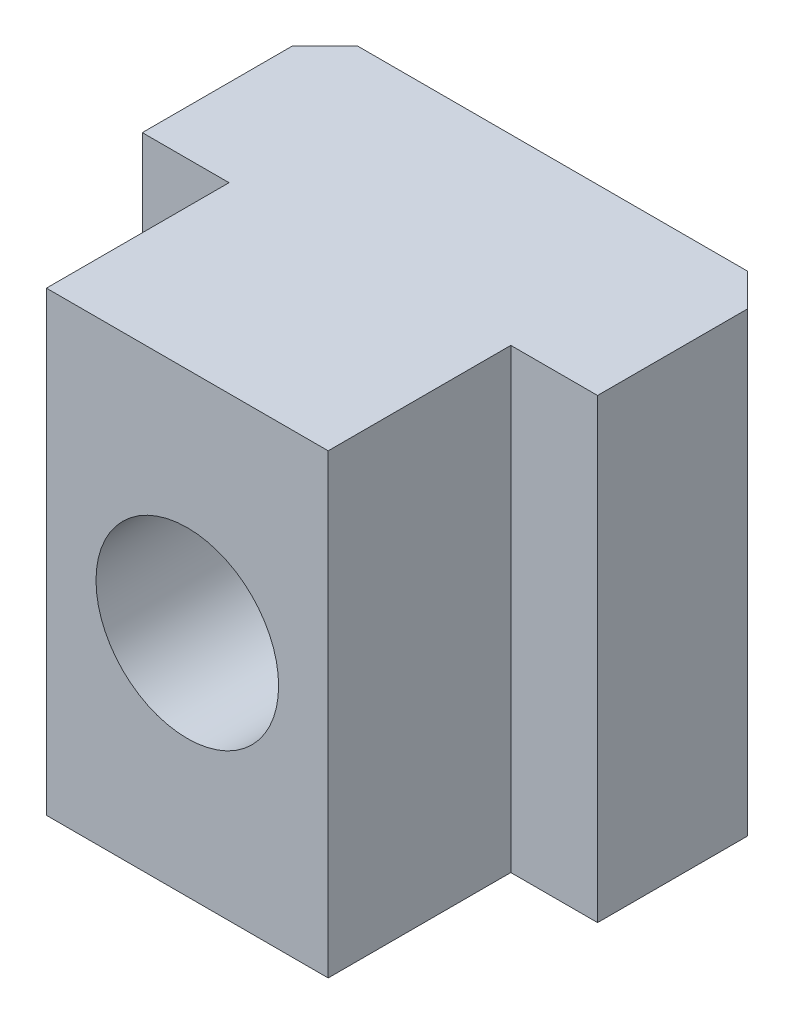
SolidWorks part; units mm, degrees
material "1.0553 (S355J0)"
ref_plane "XY Plane" through (0, 0, 0) normal (0, 0, 1) x (1, 0, 0)
ref_plane "XZ Plane" through (0, 0, 0) normal (0, 1, 0) x (1, 0, 0)
ref_plane "YZ Plane" through (0, 0, 0) normal (1, 0, 0) x (0, 0, -1)
sketch "Sketch1" plane through (0, 0, 0) normal (0, 1, 0) x (1, 0, 0)
  line L0 (-10.8, 0) -> (-17.45, 0)
  line L1 (-17.45, 0) -> (-17.45, 11.5)
  line L2 (-14.95, 14) -> (14.95, 14)
  line L3 (17.45, 11.5) -> (17.45, 0)
  line L4 (17.45, 0) -> (10.8, 0)
  line L5 (10.8, 0) -> (10.8, -14)
  line L6 (10.8, -14) -> (-10.8, -14)
  line L7 (-10.8, -14) -> (-10.8, 0)
  line L8 (0, -22.8019) -> (0, 20.8028) construction
  line L9 (-10.8, 0) -> (10.8, 0) construction
  line L10 (-17.45, 11.5) -> (-14.95, 14)
  line L11 (14.95, 14) -> (17.45, 11.5)
  point P4 (-17.45, 14)
  point P5 (17.45, 14)
  dimension "D1" = 14
  dimension "D2" = 28
  dimension "D3" = 21.6
  dimension "D4" = 34.9
extrude "Boss-Extrude1" add sketch "Sketch1" along normal mid plane 35
hole_wizard "M16 Tapped Hole1" positions "Sketch2" profile "Sketch3" tap size "M16" standard "ISO" end condition through all
sketch "Sketch2" plane through (0, 0, 14) normal (0, 0, 1) x (1, 0, 0)
  point P0 (0, 0)
sketch "Sketch3" plane through (0, 0, 14) normal (1, 0, 0) x (0, -1, 0)
  line L0 (0, 0) -> (0, 28)
  line L1 (0, 28) -> (7, 28)
  line L2 (7, 28) -> (7, 0)
  line L5 (7, 0) -> (0, 0)
  line L11 (0, -6.35) -> (0, 107.95) construction
  dimension "Thru Tap Drill Dia." = 14
  dimension "Thru Tap Drill Depth" = 28
cosmetic thread "Hole Thread1" parameters "D2"=16
